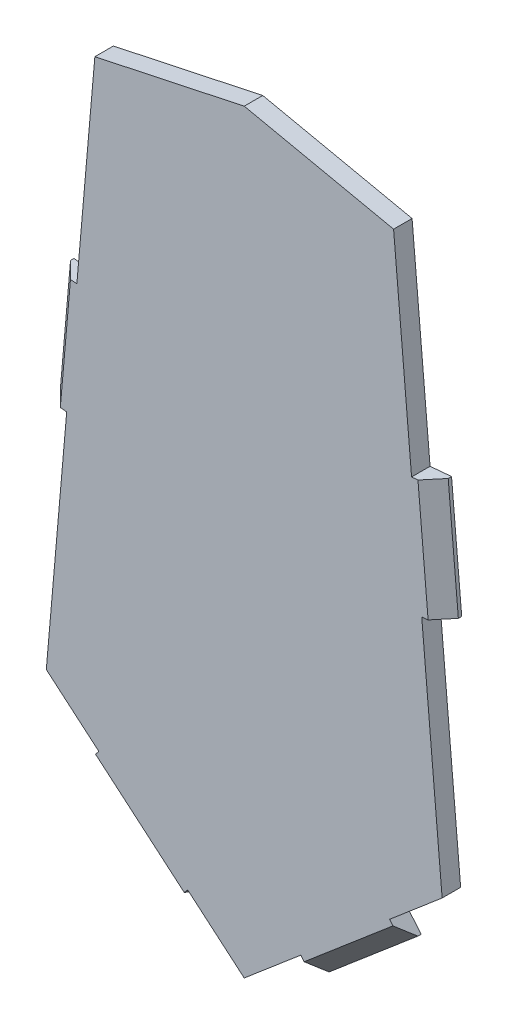
SolidWorks part; units mm, degrees
ref_plane "Front Plane" through (0, 0, 0) normal (0, 0, 1) x (1, 0, 0)
ref_plane "Top Plane" through (0, 0, 0) normal (0, 1, 0) x (1, 0, 0)
ref_plane "Right Plane" through (0, 0, 0) normal (1, 0, 0) x (0, 0, -1)
sketch "Sketch2" plane through (0, 0, 0) normal (0, 0, 1) x (1, 0, 0)
  line L0 (0, 64.8887) -> (0, -64.6913) construction
  line L1 (0, 64.8887) -> (-25.6344, 59.4259)
  line L2 (-25.6344, 59.4259) -> (-33.9676, -35.8235)
  line L3 (-33.9676, -35.8235) -> (0, -64.6913)
  line L4 (0, -64.6913) -> (33.9676, -35.8235)
  line L5 (33.9676, -35.8235) -> (25.6344, 59.4259)
  line L6 (25.6344, 59.4259) -> (0, 64.8887)
  line L7 (-33.9676, -35.8235) -> (33.9676, -35.8235) construction
  line L8 (28.7217, 24.1375) -> (32.4076, 24.46)
  line L9 (32.4076, 24.46) -> (34.1508, 4.5361)
  line L10 (34.1508, 4.5361) -> (30.4648, 4.2136)
  line L11 (30.4648, 4.2136) -> (28.7217, 24.1375)
  line L12 (-28.7217, 24.1375) -> (-32.4076, 24.46)
  line L13 (-32.4076, 24.46) -> (-34.1508, 4.5361)
  line L14 (-34.1508, 4.5361) -> (-30.4648, 4.2136)
  line L15 (-30.4648, 4.2136) -> (-28.7217, 24.1375)
  line L16 (9.6982, -56.4491) -> (11.9648, -59.1161)
  line L17 (11.9648, -59.1161) -> (27.2046, -46.1643)
  line L18 (27.2046, -46.1643) -> (24.938, -43.4974)
  line L19 (24.938, -43.4974) -> (9.6982, -56.4491)
  line L20 (-24.938, -43.4974) -> (-27.2046, -46.1643)
  line L21 (-27.2046, -46.1643) -> (-11.9648, -59.1161)
  line L22 (-11.9648, -59.1161) -> (-9.6982, -56.4491)
  line L23 (-9.6982, -56.4491) -> (-24.938, -43.4974)
  dimension "D1" = 129.58
  dimension "D2" = 26.21
  dimension "D3" = 26.21
  dimension "D4" = 155.94
  dimension "D5" = 107.03
  dimension "D6" = 107.03
  dimension "D7" = 125.36
  dimension "D8" = 3.5
  dimension "D10" = 3.5
  dimension "D11" = 20
  dimension "D12" = 11.85
  dimension "D13" = 11.85
  dimension "D14" = 20
  dimension "D15" = 3.5
  dimension "D16" = 20
  dimension "D17" = 3.7
  dimension "D18" = 20
  dimension "D19" = 3.7
  dimension "D20" = 40.19
  dimension "D21" = 40.19
extrude "Boss-Extrude2" add sketch "Sketch2" along normal blind 3.175 contours L5 L6 L1 L2 L3 L4 | L13 L14 L2 L12 | L10 L9 L8 L5 | L17 L18 L4 L16 | L21 L22 L3 L20
chamfer "Chamfer3" distance 2.6 angle 45 4 edges at (-33.2792, 14.498, 3.175) (33.2792, 14.498, 3.175) (19.5847, -52.6402, 3.175) (-19.5847, -52.6402, 3.175)
